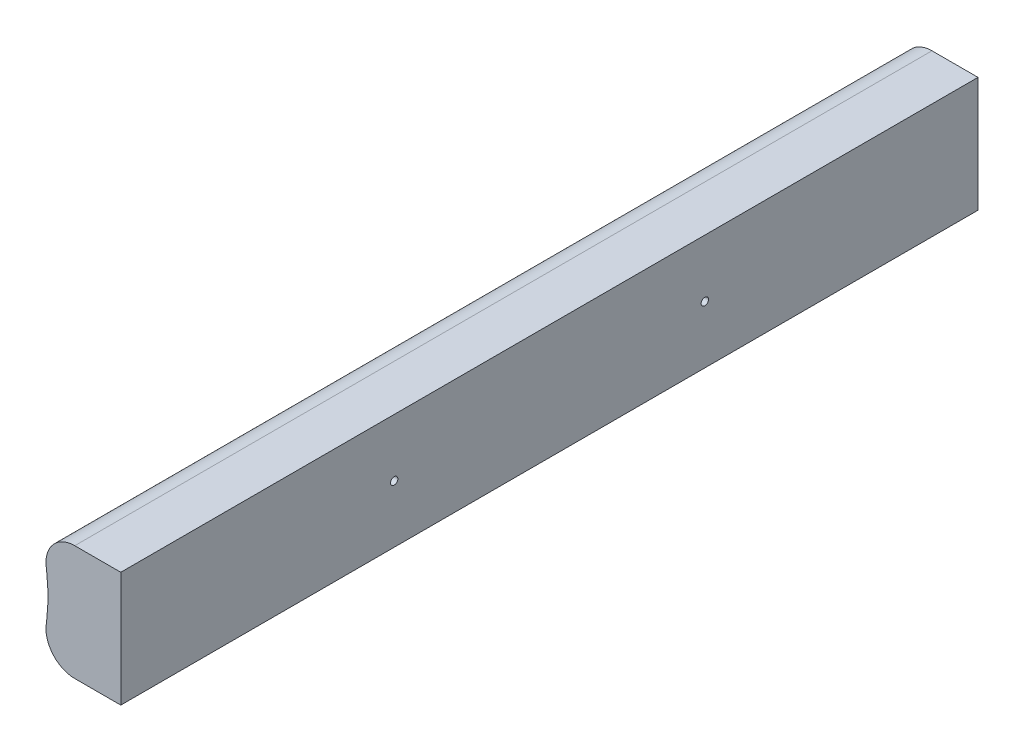
SolidWorks part; units mm, degrees
ref_plane "Front" through (0, 0, 0) normal (0, 0, 1) x (1, 0, 0)
ref_plane "Top" through (0, 0, 0) normal (0, 1, 0) x (1, 0, 0)
ref_plane "Right" through (0, 0, 0) normal (1, 0, 0) x (0, 0, -1)
sketch "Sketch1" plane through (0, 0, 0) normal (0, 0, 1) x (1, 0, 0)
  line L0 (-81.456, -19.8133) -> (-82.3706, -28.3793)
  line L1 (-50.8, -63.5) -> (0, -63.5)
  line L2 (0, -63.5) -> (0, 63.5)
  line L3 (0, 63.5) -> (-50.8, 63.5)
  line L4 (-82.3706, 28.3793) -> (-81.456, 19.8133)
  line L5 (0, 0) -> (-160.6881, 0) construction
  line L6 (-50.8, 96.0303) -> (-50.8, -98.1367) construction
  arc A0 (-82.3706, -28.3793) -> (-50.8, -63.5) centre (-50.8, -31.75) ccw
  arc A1 (-50.8, 63.5) -> (-82.3706, 28.3793) centre (-50.8, 31.75) ccw
  arc A2 (-81.456, -19.8133) -> (-81.456, 19.8133) centre (-267.0315, 0) ccw
  dimension "D2" = 31.75
  dimension "D4" = 186.6302
  dimension "D5" = 50.8
  dimension "D6" = 80.4013
  dimension "D1" = 127
extrude "Extrude1" add sketch "Sketch1" along normal mid plane 946.15
hole_wizard "A (0.234) Diameter Hole1" positions "3DSketch1" profile "Sketch2" hole size "A" standard "Ansi (в дюймах)"
sketch3d "3DSketch1"
  line L1 (0, -63.5, 473.075) -> (0, 63.5, 473.075) construction
  point P0 (0, 0, 171.323)
  point P2 (0, 0, -171.577)
  dimension "D1" = 342.9
  dimension "D2" = 301.752
sketch "Sketch2" plane through (0, 0, 171.323) normal (0, 1, 0) x (0, 0, -1)
  line L0 (0, 0) -> (0, 21.4919)
  line L1 (0, 21.4919) -> (4.064, 19.05)
  line L2 (4.064, 19.05) -> (4.064, 0)
  line L5 (4.064, 0) -> (0, 0)
  line L10 (0, 21.4919) -> (-4.064, 19.05) construction
  line L11 (0, -6.35) -> (0, 107.95) construction
  dimension "Диаметр отверстия" = 8.128
  dimension "Глубина отверстия" = 19.05
  dimension "Угол заточки сверла" = 118
